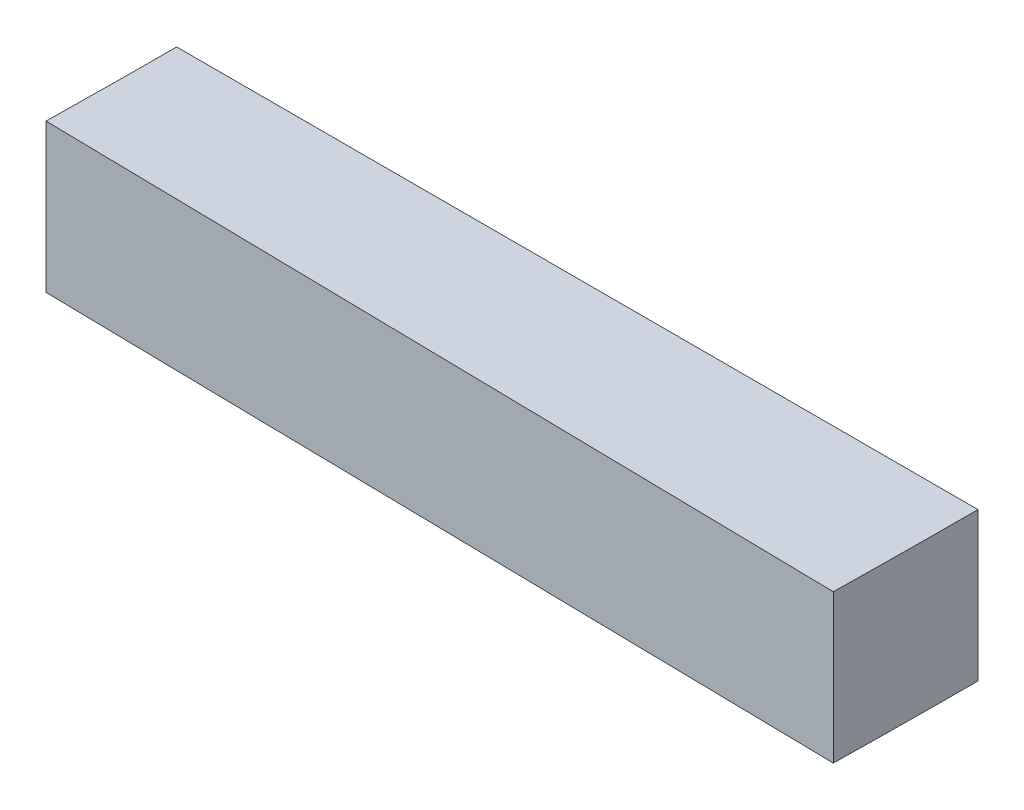
SolidWorks part; units mm, degrees
ref_plane "Front Plane" through (0, 0, 0) normal (0, 0, 1) x (1, 0, 0)
ref_plane "Top Plane" through (0, 0, 0) normal (0, 1, 0) x (1, 0, 0)
ref_plane "Right Plane" through (0, 0, 0) normal (1, 0, 0) x (0, 0, -1)
other "Configuration Table"
sketch "Sketch1" plane through (0, 0, 0) normal (0, 0, 1) x (1, 0, 0)
  line L0 (-127, 22.1502) -> (-127, -21.6598) construction
  line L1 (0, 0) -> (13.716, 0)
  line L2 (0, 0) -> (0, 2.54)
  line L3 (0, 2.54) -> (13.716, 2.54)
  line L4 (13.716, 0) -> (13.716, 2.54)
  dimension "D1" = 13.716
  dimension "D2" = 2.54
  dimension "D3" = 127
revolve "Revolve1" add sketch "Sketch1" angle 1 about L0
